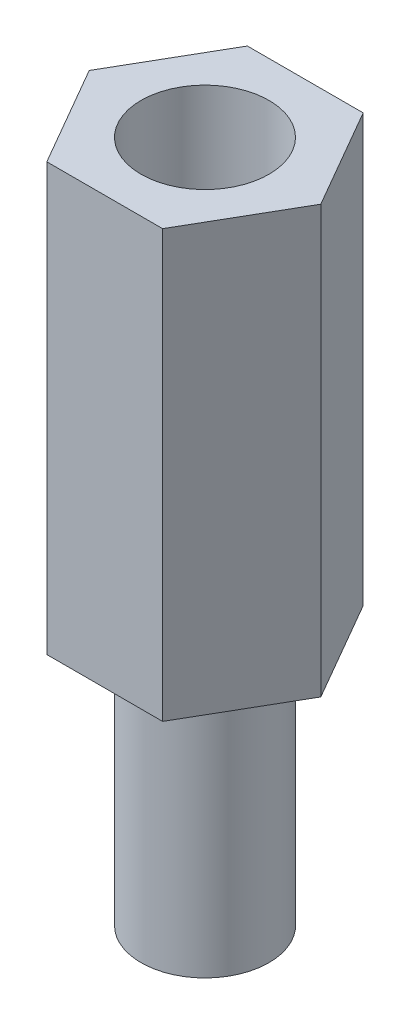
SolidWorks part; units mm, degrees
material "黄铜"
ref_plane "前视基准面" through (0, 0, 0) normal (0, 0, 1) x (1, 0, 0)
ref_plane "上视基准面" through (0, 0, 0) normal (0, 1, 0) x (1, 0, 0)
ref_plane "右视基准面" through (0, 0, 0) normal (1, 0, 0) x (0, 0, -1)
sketch "草图1" plane through (0, 0, 0) normal (0, 1, 0) x (1, 0, 0)
  line L1 (2.7135, 0) -> (1.3568, 2.35)
  line L2 (1.3568, 2.35) -> (-1.3568, 2.35)
  line L3 (-1.3568, 2.35) -> (-2.7135, 0)
  line L4 (-2.7135, 0) -> (-1.3568, -2.35)
  line L5 (-1.3568, -2.35) -> (1.3568, -2.35)
  line L6 (1.3568, -2.35) -> (2.7135, 0)
  circle A0 centre (0, 0) radius 1.5
  circle A1 centre (0, 0) radius 2.35 construction
  dimension "D1" = 3
  dimension "D2" = 4.7
extrude "凸台-拉伸1" add sketch "草图1" along normal blind 10
sketch "草图2" plane through (0, 0, 0) normal (0, -1, 0) x (-1, 0, 0)
  circle A0 centre (0, 0) radius 1.5
extrude "凸台-拉伸2" add sketch "草图2" along normal blind 6 separate body
